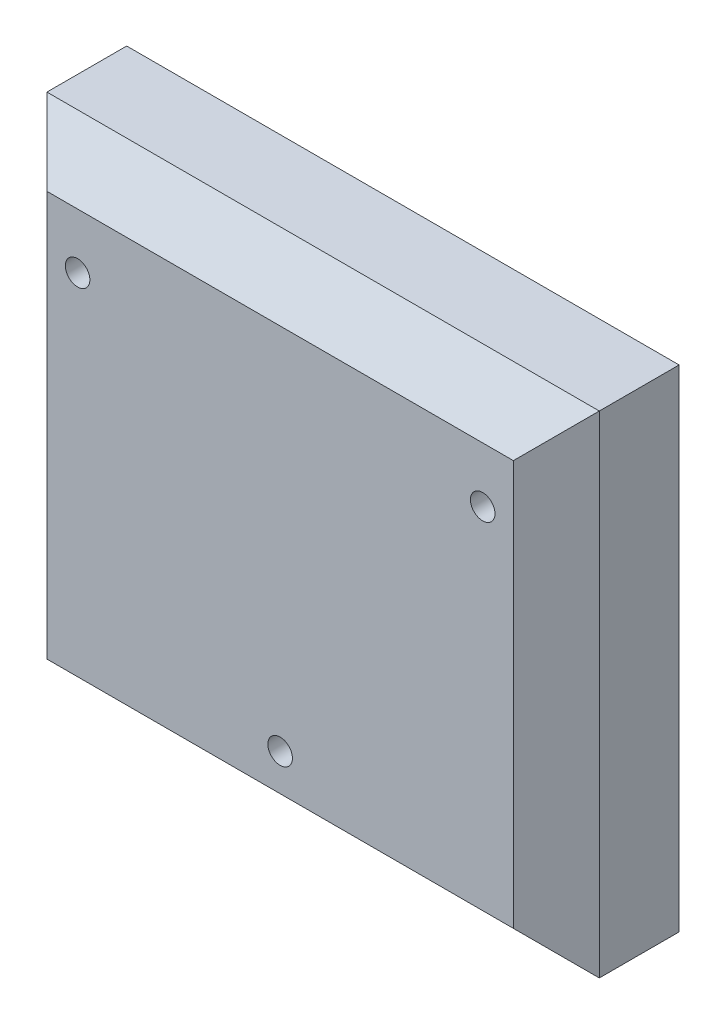
SolidWorks part; units mm, degrees
material "Maple"
ref_plane "Front Plane" through (0, 0, 0) normal (0, 0, 1) x (1, 0, 0)
ref_plane "Top Plane" through (0, 0, 0) normal (0, 1, 0) x (1, 0, 0)
ref_plane "Right Plane" through (0, 0, 0) normal (1, 0, 0) x (0, 0, -1)
sketch "Sketch1" plane through (0, 0, 0) normal (0, 0, 1) x (1, 0, 0)
  line L0 (0, 0) -> (0, 29.399) construction
  line L1 (0, 0) -> (0, -21.2456) construction
  line L2 (0, 0) -> (38.4146, 0) construction
  line L3 (0, 0) -> (-28.6934, 0) construction
  line L4 (0, 0) -> (45, 0)
  line L5 (0, 0) -> (-40.2962, 0)
  dimension "D1" = 45
  dimension "D2" = 40.2962
sketch "Sketch5" plane through (0, 0, 0) normal (0, 0, 1) x (1, 0, 0)
  line L0 (-45, 34.2576) -> (45, 34.2576)
  line L1 (45, 34.2576) -> (45, -45.7424)
  line L2 (45, -45.7424) -> (-45, -45.7424)
  line L3 (-45, -45.7424) -> (-45, 34.2576)
  dimension "D1" = 90
  dimension "D2" = 80
  dimension "D3" = 45
extrude "Boss-Extrude4" add sketch "Sketch5" along normal blind 13
sketch "Sketch6" plane through (0, -45.7424, 0) normal (0, -1, 0) x (1, 0, 0)
  line L0 (-45, 13) -> (-38, 20)
  line L1 (-45, 13) -> (45, 13) construction
  line L2 (45, 13) -> (38, 20)
  line L3 (-38, 20) -> (38, 20)
  line L8 (-45, 0) -> (45, 0)
  line L9 (45, 0) -> (45, 13)
  line L10 (45, 13) -> (-45, 13)
  line L11 (-45, 13) -> (-45, 0)
  line L12 (-45, 0) -> (45, 0)
  line L13 (45, 0) -> (45, 13)
  line L15 (-45, 13) -> (-45, 0)
  dimension "D1" = 45
  dimension "D2" = 45
  dimension "D3" = 20
  dimension "D4" = 20
  dimension "D5" = 0
extrude "Boss-Extrude5" add sketch "Sketch6" against normal through all contours L12 L13 L2 L3 L0 L15
chamfer "Chamfer1" distance 7 angle 45 2 edges at (0, -45.7424, 20) (0, 34.2576, 20)
sketch "Sketch13" plane through (0, 0, 0) normal (0, 0, -1) x (-1, 0, 0)
  line L0 (0, -21.2456) -> (0, -45.7424)
  line L1 (45, -45.7424) -> (-45, -45.7424) construction
  circle A0 centre (0, -32.7424) radius 2
  dimension "D2" = 4
  dimension "D1" = 13
sketch "Sketch14" plane through (0, 0, 0) normal (0, 0, -1) x (-1, 0, 0)
  line L0 (-39.453, 18.2576) -> (36.375, 18.2576)
  line L1 (-45, 34.2576) -> (45, 34.2576) construction
  line L2 (0, 0) -> (0, 29.399) construction
  circle A0 centre (-33, 18.2576) radius 2
  circle A1 centre (33, 18.2576) radius 2
  dimension "D4" = 4
  dimension "D5" = 4
  dimension "D1" = 16
  dimension "D2" = 33
  dimension "D3" = 33
extrude "Cut-Extrude4" cut sketch "Sketch13" against normal up to vertex (20 mm away) contours A0
extrude "Cut-Extrude8" cut sketch "Sketch14" against normal up to vertex (20 mm away) contours A0 | A1
